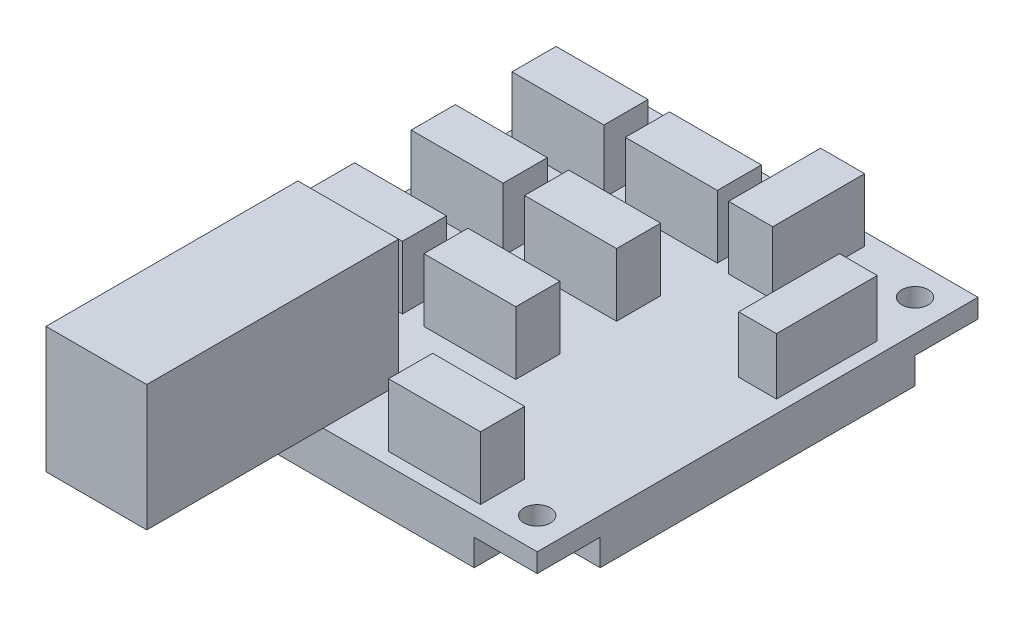
SolidWorks part; units mm, degrees
material "5052-H38"
ref_plane "Front" through (0, 0, 0) normal (0, 0, 1) x (1, 0, 0)
ref_plane "Top" through (0, 0, 0) normal (0, 1, 0) x (1, 0, 0)
ref_plane "Right" through (0, 0, 0) normal (1, 0, 0) x (0, 0, -1)
sketch "ｽｹｯﾁ1" plane through (0, 0, 0) normal (0, 1, 0) x (1, 0, 0)
  line L1 (-15, 17.5) -> (15, 17.5)
  line L2 (-15, 17.5) -> (-15, -17.5)
  line L3 (-15, -17.5) -> (15, -17.5)
  line L4 (15, 17.5) -> (15, -17.5)
  line L5 (-15, 17.5) -> (15, -17.5) construction
  line L6 (-15, -17.5) -> (15, 17.5) construction
  point P0 (0, 0)
  dimension "D1" = 30
  dimension "D2" = 35
extrude "ﾎﾞｽ - 押し出し1" add sketch "ｽｹｯﾁ1" along normal mid plane 1.5
sketch "ｽｹｯﾁ2" plane through (0, -0.75, 0) normal (0, -1, 0) x (1, 0, 0)
  line L1 (-12.5, 15) -> (12.5, 15) construction
  line L2 (-12.5, 15) -> (-12.5, -15) construction
  line L3 (-12.5, -15) -> (12.5, -15) construction
  line L4 (12.5, 15) -> (12.5, -15) construction
  line L5 (-12.5, 15) -> (12.5, -15) construction
  line L6 (-12.5, -15) -> (12.5, 15) construction
  circle A0 centre (-12.5, 15) radius 1.05
  circle A1 centre (-12.5, -15) radius 1.05
  circle A2 centre (12.5, 15) radius 1.05
  circle A3 centre (12.5, -15) radius 1.05
  point P5 (0, 0)
  dimension "D1" = 2.1
  dimension "D2" = 2.1
  dimension "D3" = 2.1
  dimension "D4" = 2.1
  dimension "D5" = 25
  dimension "D6" = 30
extrude "ｶｯﾄ - 押し出し1" cut sketch "ｽｹｯﾁ2" against normal blind 1.5
sketch "ｽｹｯﾁ3" plane through (0, -0.75, 0) normal (0, -1, 0) x (1, 0, 0)
  line L0 (-10, 17.5) -> (-10, 13.5)
  line L1 (-15, 17.5) -> (15, 17.5) construction
  line L3 (-15, -17.5) -> (-15, 17.5) construction
  line L4 (-15, 13.5) -> (-15, -12.5)
  line L5 (-15, -12.5) -> (-10, -12.5)
  line L6 (-10, -12.5) -> (-10, -17.5)
  line L7 (15, -17.5) -> (-15, -17.5) construction
  line L8 (-10, -17.5) -> (10, -17.5)
  line L9 (10, -17.5) -> (10, -12.5)
  line L10 (10, -12.5) -> (15, -12.5)
  line L11 (15, 17.5) -> (15, -17.5) construction
  line L12 (15, -12.5) -> (15, 12.5)
  line L13 (15, 12.5) -> (10, 12.5)
  line L14 (10, 12.5) -> (10, 17.5)
  line L15 (10, 17.5) -> (-10, 17.5)
  line L16 (-15, 13.5) -> (-10, 13.5)
  circle A0 centre (-12.5, 15) radius 1.05 construction
  circle A1 centre (-12.5, -15) radius 1.05 construction
  circle A2 centre (12.5, 15) radius 1.05 construction
  dimension "D5" = 1.5
  dimension "D1" = 2.5
  dimension "D2" = 2.5
  dimension "D3" = 2.5
  dimension "D4" = 2.5
extrude "ﾎﾞｽ - 押し出し2" add sketch "ｽｹｯﾁ3" along normal blind 2.1
sketch "ｽｹｯﾁ4" plane through (0, 0.75, 0) normal (0, 1, 0) x (1, 0, 0)
  line L0 (15, 17.5) -> (-15, 17.5) construction
  line L1 (-14, 13) -> (-6.7, 13)
  line L2 (-14, 13) -> (-14, 9.5)
  line L3 (-14, 9.5) -> (-6.7, 9.5)
  line L4 (-6.7, 13) -> (-6.7, 9.5)
  line L5 (-14, 13) -> (-6.7, 9.5) construction
  line L6 (-14, 9.5) -> (-6.7, 13) construction
  line L11 (-15, -17.5) -> (15, -17.5) construction
  line L12 (15, -17.5) -> (15, 17.5) construction
  line L13 (3.5, 9.2) -> (7, 9.2)
  line L14 (3.5, 9.2) -> (3.5, 16.5)
  line L15 (3.5, 16.5) -> (7, 16.5)
  line L16 (7, 9.2) -> (7, 16.5)
  line L17 (3.5, 9.2) -> (7, 16.5) construction
  line L18 (3.5, 16.5) -> (7, 9.2) construction
  line L19 (2.2, -13) -> (9.5, -13)
  line L20 (2.2, -13) -> (2.2, -16.5)
  line L21 (2.2, -16.5) -> (9.5, -16.5)
  line L22 (9.5, -13) -> (9.5, -16.5)
  line L23 (2.2, -13) -> (9.5, -16.5) construction
  line L24 (2.2, -16.5) -> (9.5, -13) construction
  line L49 (-15, 17.5) -> (-15, -17.5) construction
  point P4 (-10.35, 11.25)
  point P14 (5.25, 12.85)
  point P19 (5.85, -14.75)
  dimension "D1" = 7.3
  dimension "D2" = 3.5
  dimension "D3" = 4.5
  dimension "D4" = 1
  dimension "D5" = 1
  dimension "D6" = 5.5
  dimension "D7" = 1
  dimension "D8" = 8
extrude "ﾎﾞｽ - 押し出し3" add sketch "ｽｹｯﾁ4" along normal blind 5 contours L13 L16 L15 L14 | L22 L19 L20 L21
sketch "ｽｹｯﾁ5" plane through (0, 0.75, 0) normal (0, 1, 0) x (1, 0, 0)
  line L0 (15, 17.5) -> (-15, 17.5) construction
  line L1 (-14, 13) -> (-6.7, 13)
  line L2 (-14, 13) -> (-14, 9.5)
  line L3 (-14, 9.5) -> (-6.7, 9.5)
  line L4 (-6.7, 13) -> (-6.7, 9.5)
  line L5 (-14, 13) -> (-6.7, 9.5) construction
  line L6 (-14, 9.5) -> (-6.7, 13) construction
  line L7 (-15, 17.5) -> (-15, -17.5) construction
  line L8 (7, 9.2) -> (7, 16.5) construction
  line L9 (3.5, 9.2) -> (7, 9.2) construction
  point P4 (-10.35, 11.25)
  dimension "D1" = 4.5
  dimension "D2" = 1
extrude "ﾎﾞｽ - 押し出し4" add sketch "ｽｹｯﾁ5" along normal up to surface (5 mm away) up to face at (5.25, 5.75, -12.85)
pattern_linear "直線ﾊﾟﾀｰﾝ1" count 2 spacing 9 along (1, 0, 0) of "ﾎﾞｽ - 押し出し4"
pattern_linear "直線ﾊﾟﾀｰﾝ2" count 3 spacing 8 along (0, 0, 1) of "ﾎﾞｽ - 押し出し4", "直線ﾊﾟﾀｰﾝ1"
sketch "ｽｹｯﾁ6" plane through (0, 0.75, 0) normal (0, 1, 0) x (1, 0, 0)
  line L0 (15, 17.5) -> (-15, 17.5) construction
  line L1 (11, 10.5) -> (14, 10.5)
  line L2 (11, 10.5) -> (11, 2.5)
  line L3 (11, 2.5) -> (14, 2.5)
  line L4 (14, 10.5) -> (14, 2.5)
  line L5 (11, 10.5) -> (14, 2.5) construction
  line L6 (11, 2.5) -> (14, 10.5) construction
  line L7 (15, -17.5) -> (15, 17.5) construction
  point P4 (12.5, 6.5)
  dimension "D1" = 7
  dimension "D2" = 8
  dimension "D3" = 3
  dimension "D4" = 1
extrude "ﾎﾞｽ - 押し出し5" add sketch "ｽｹｯﾁ6" along normal blind 4.5
sketch "ｽｹｯﾁ7" plane through (0, 0.75, 0) normal (0, 1, 0) x (1, 0, 0)
  line L0 (-15, -17.5) -> (15, -17.5) construction
  line L1 (-10, -11.5) -> (-2, -11.5)
  line L2 (-10, -11.5) -> (-10, -31.5)
  line L3 (-10, -31.5) -> (-2, -31.5)
  line L4 (-2, -11.5) -> (-2, -31.5)
  line L5 (-10, -11.5) -> (-2, -31.5) construction
  line L6 (-10, -31.5) -> (-2, -11.5) construction
  line L8 (-15, 17.5) -> (-15, -17.5) construction
  point P4 (-6, -21.5)
  dimension "D1" = 14
  dimension "D2" = 6
  dimension "D3" = 9
  dimension "D4" = 8
extrude "ﾎﾞｽ - 押し出し6" add sketch "ｽｹｯﾁ7" along normal blind 10
